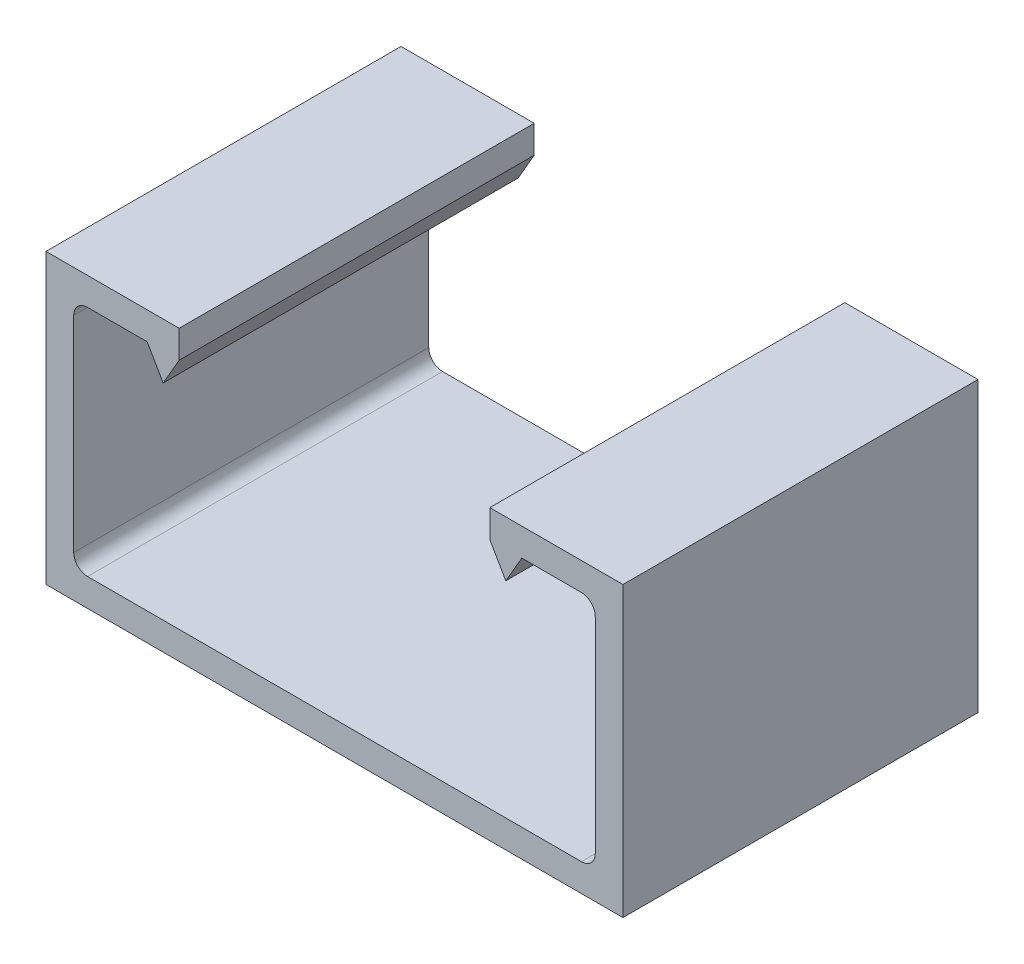
SolidWorks part; units mm, degrees
ref_plane "Plane1" through (0, 0, 0) normal (0, 0, 1) x (1, 0, 0)
ref_plane "Plane2" through (0, 0, 0) normal (0, 1, 0) x (1, 0, 0)
ref_plane "Plane3" through (0, 0, 0) normal (1, 0, 0) x (0, 0, -1)
sketch "Sketch1" plane through (0, 0, 0) normal (0, 0, 1) x (1, 0, 0)
  line L0 (-11.1125, 10.3187) -> (-20.6375, 10.3187)
  line L1 (-20.6375, 10.3187) -> (-20.6375, -10.3187)
  line L2 (-20.6375, -10.3187) -> (20.6375, -10.3187)
  line L3 (20.6375, -10.3187) -> (20.6375, 10.3188)
  line L4 (20.6375, 10.3188) -> (11.1125, 10.3188)
  line L5 (17.6657, 8.3376) -> (13.4002, 8.3376)
  line L6 (18.6563, -7.3469) -> (18.6563, 7.347)
  line L7 (-17.6657, -8.3375) -> (17.6657, -8.3375)
  line L8 (-18.6563, 7.3469) -> (-18.6563, -7.3469)
  line L9 (-13.4002, 8.3375) -> (-17.6657, 8.3375)
  line L10 (13.4002, 8.3376) -> (12.2563, 6.3564)
  line L11 (12.2563, 6.3564) -> (11.1125, 8.3376)
  line L12 (11.1125, 8.3376) -> (11.1125, 10.3188)
  line L13 (-13.4002, 8.3375) -> (-12.2563, 6.3564)
  line L14 (-12.2563, 6.3564) -> (-11.1125, 8.3376)
  line L15 (-11.1125, 8.3376) -> (-11.1125, 10.3187)
  arc A0 (-18.6563, -7.3469) -> (-17.6657, -8.3375) centre (-17.6657, -7.3469) ccw
  arc A1 (-17.6657, 8.3375) -> (-18.6563, 7.3469) centre (-17.6657, 7.3469) ccw
  arc A2 (18.6563, 7.347) -> (17.6657, 8.3376) centre (17.6657, 7.347) ccw
  arc A3 (17.6657, -8.3375) -> (18.6563, -7.3469) centre (17.6657, -7.3469) ccw
  dimension "D5" = 0.9906
  dimension "Width" = 41.275
  dimension "Height" = 20.6375
  dimension "D8" = 20.6375
  dimension "D9" = 10.3187
  dimension "D10" = 22.225
  dimension "edge" = 9.525
  dimension "D13" = 1.1438
  dimension "D4" = 60
extrude "Base-Extrude" add sketch "Sketch1" along normal mid plane 25.4
equation "\"D8@Sketch1\" = \"Width@Sketch1\" / 2"
equation "\"D9@Sketch1\" = \"Height@Sketch1\" / 2"
equation "\"D10@Sketch1\" = \"Width@Sketch1\" - 2 * \"edge@Sketch1\""
equation "\"D5@Sketch1\" = \"gauge@Sketch1\" / 2"
equation "\"D13@Sketch1\" = \"gauge@Sketch1\" * .577350269"
